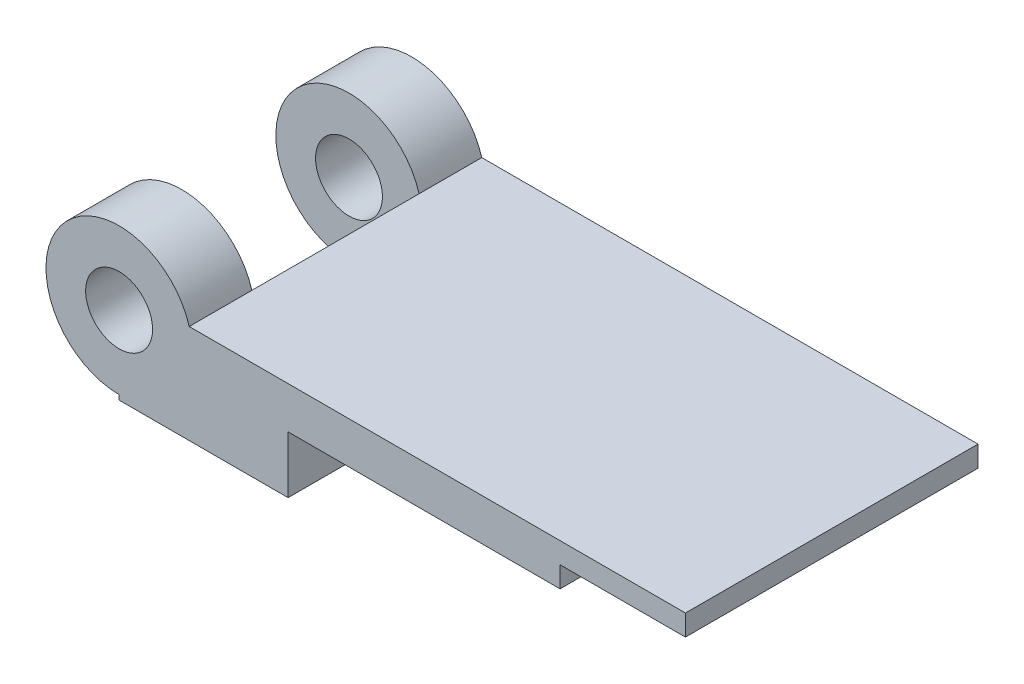
SolidWorks part; units mm, degrees
ref_plane "Front Plane" through (0, 0, 0) normal (0, 0, 1) x (1, 0, 0)
ref_plane "Top Plane" through (0, 0, 0) normal (0, 1, 0) x (1, 0, 0)
ref_plane "Right Plane" through (0, 0, 0) normal (1, 0, 0) x (0, 0, -1)
other "Configuration Table"
sketch "草图1" plane through (0, 0, 0) normal (0, 0, 1) x (1, 0, 0)
  line L0 (0, 0) -> (18.3218, 0) construction
  line L1 (3.3541, 1) -> (27.1, 1)
  line L2 (3.3541, -1) -> (27.1, -1)
  line L3 (27.1, 1) -> (27.1, -1)
  circle A0 centre (0, 0) radius 1.6
  arc A1 (3.3541, 1) -> (3.3541, -1) centre (0, 0) ccw
  circle A2 centre (0, 0) radius 2.75 construction
  dimension "D1" = 3.2
  dimension "D2" = 7
  dimension "D4" = 5.5
  dimension "D5" = 27.1
  dimension "D3" = 1
extrude "凸台-拉伸1" add sketch "草图1" along normal blind 14
sketch "草图2" plane through (0, 0, 14) normal (0, 0, 1) x (1, 0, 0)
  line L0 (27.1, 0) -> (21.1, 0)
  line L1 (27.1, -1) -> (27.1, 1) construction
  line L2 (21.1, 0) -> (21.1, -1)
  line L3 (3.3541, -1) -> (27.1, -1) construction
  line L4 (21.1, -1) -> (27.1, -1)
  line L5 (27.1, -1) -> (27.1, 0)
  dimension "D1" = 6
extrude "切除-拉伸1" cut sketch "草图2" against normal blind 14
ref_plane "基准面1" through (0, 0, 7) normal (0, 0, 1) x (1, 0, 0)
sketch "草图3" plane through (0, 0, 7) normal (0, 0, 1) x (1, 0, 0)
  circle A0 centre (0, 0) radius 1.6
  circle A1 centre (0, 0) radius 3.5
  arc A2 (3.3541, 1) -> (3.3541, -1) centre (0, 0) ccw construction
extrude "切除-拉伸2" cut sketch "草图3" against normal mid plane 8
sketch "草图6" plane through (0, 0, 14) normal (0, 0, 1) x (1, 0, 0)
  line L0 (0, -2.75) -> (8.0855, -2.75) construction
  line L2 (8.0855, -2.1) -> (8.0855, -3.4)
  line L4 (8.0855, -2.1) -> (8.0855, -1)
  line L5 (3.3541, -1) -> (21.1, -1) construction
  line L6 (8.0855, -1) -> (3.3541, -1)
  line L8 (8.0855, -3.5) -> (8.0855, -3.4)
  line L9 (0, -3.5) -> (0, -3.7281)
  line L10 (0, -3.7281) -> (8.0855, -3.7281)
  line L11 (8.0855, -3.7281) -> (8.0855, -3.5)
  circle A0 centre (0, 0) radius 2.75 construction
  arc A5 (3.3541, 1) -> (3.3541, -1) centre (0, 0) ccw construction
  arc A6 (0, -3.5) -> (3.3541, -1) centre (0, 0) ccw
  point P8 (8.0855, -2.75)
  dimension "D1" = 5.5
  dimension "D2" = 1.3
extrude "凸台-拉伸2" add sketch "草图6" against normal up to surface (14 mm away) up to face at (16.0424, 0, 0)
sketch "草图8" plane through (8.0855, 0, 0) normal (1, 0, 0) x (0, 0, -1)
  line L0 (-14, -2.364) -> (0, -2.364) construction
  line L3 (-11, -1.814) -> (-11, -2.914)
  line L4 (-11, -2.914) -> (-3, -2.914)
  line L5 (-3, -2.914) -> (-3, -1.814)
  line L6 (-3, -1.814) -> (-11, -1.814)
  line L7 (-11, -3.5) -> (-11, 3.5) construction
  line L8 (-3, 3.5) -> (-3, -3.5) construction
  line L9 (0, -1) -> (0, -3.7281) construction
  point P10 (-3, -2.364)
  point P13 (0, -2.364)
  dimension "D1" = 1.1
sketch "草图9" plane through (0, 0, 11) normal (0, 0, 1) x (1, 0, 0)
  line L0 (0, -2.75) -> (9.0266, -2.75) construction
  line L2 (8.0855, -1.814) -> (8.0855, -2.914) construction
  line L3 (8.0855, -3.7281) -> (8.0855, -1) construction
  line L4 (8.0855, -3.35) -> (0.6644, -3.35)
  line L5 (0.6644, -3.35) -> (0.6644, -2.15)
  line L6 (0.6644, -2.15) -> (8.0855, -2.15)
  line L7 (8.0855, -2.15) -> (8.0855, -3.35)
  circle A0 centre (0, 0) radius 2.75 construction
  point P5 (0.6644, -2.75)
  dimension "D1" = 5.5
  dimension "D2" = 1.2
extrude "切除-拉伸4" cut sketch "草图9" against normal up to surface (8 mm away) up to face at (1.6, 0, 3)
